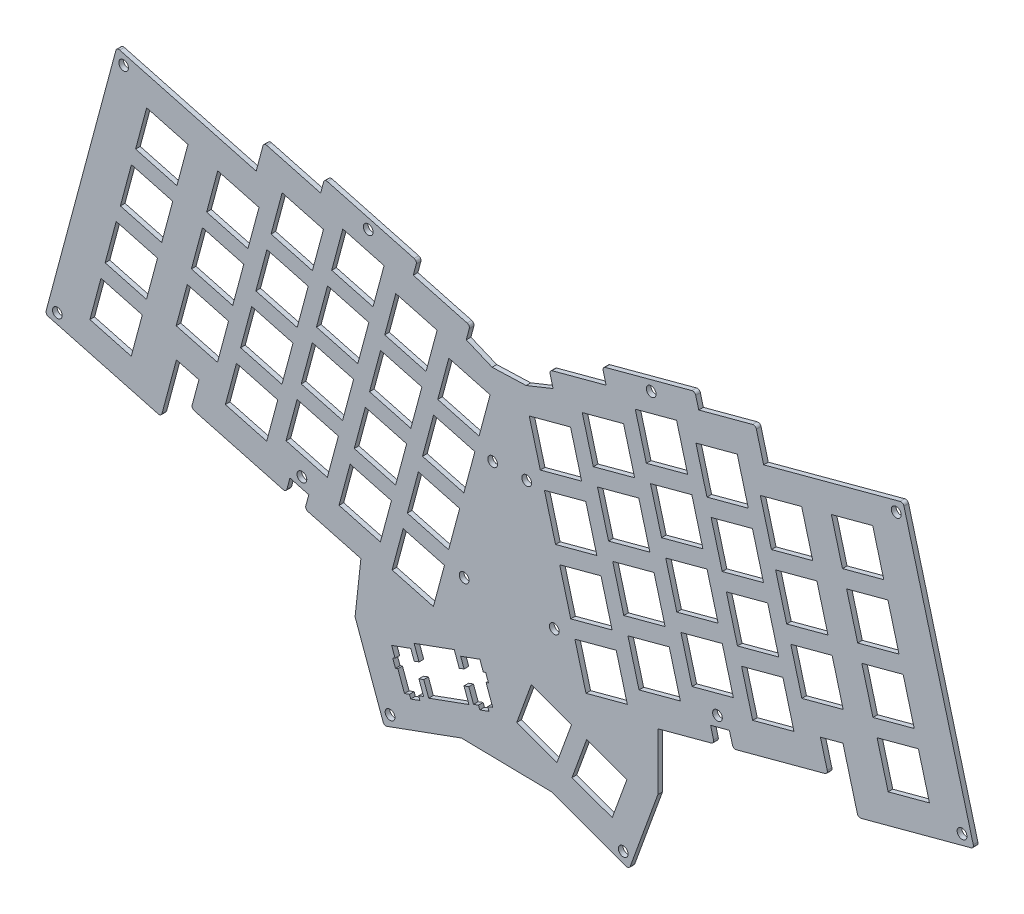
SolidWorks part; units mm, degrees
ref_plane "Front Plane" through (0, 0, 0) normal (0, 0, 1) x (1, 0, 0)
ref_plane "Top Plane" through (0, 0, 0) normal (0, 1, 0) x (1, 0, 0)
ref_plane "Right Plane" through (0, 0, 0) normal (1, 0, 0) x (0, 0, -1)
sketch "Model" plane through (0, 0, 0) normal (0, 0, 1) x (1, 0, 0)
  line L0 (282.165, 226.202) -> (288.4436, 227.8841) construction
  line L1 (267.373, 281.405) -> (273.6516, 283.0871) construction
  line L2 (195.392, 284.0785) -> (194.5766, 287.1211) construction
  line L3 (100.681, 283.685) -> (101.4961, 286.7277) construction
  line L4 (168.22, 168.742) -> (181.234, 164.006)
  line L5 (181.234, 164.006) -> (185.972, 177.021)
  line L6 (185.972, 177.021) -> (172.956, 181.758)
  line L7 (172.956, 181.758) -> (168.22, 168.742)
  line L8 (132.176, 184.752) -> (133.281, 181.717)
  line L9 (133.281, 181.717) -> (131.706, 181.144)
  line L10 (131.706, 181.144) -> (130.099, 185.56)
  line L11 (130.099, 185.56) -> (117.085, 180.823)
  line L12 (117.085, 180.823) -> (118.692, 176.407)
  line L13 (118.692, 176.407) -> (117.118, 175.834)
  line L14 (117.118, 175.834) -> (116.013, 178.869)
  line L15 (116.013, 178.869) -> (109.812, 176.612)
  line L16 (109.812, 176.612) -> (110.917, 173.576)
  line L17 (110.917, 173.576) -> (110.141, 173.294)
  line L18 (110.141, 173.294) -> (111.048, 170.804)
  line L19 (111.048, 170.804) -> (111.822, 171.086)
  line L20 (111.822, 171.086) -> (113.968, 165.194)
  line L21 (113.968, 165.194) -> (115.588, 165.784)
  line L22 (115.588, 165.784) -> (115.999, 164.656)
  line L23 (115.999, 164.656) -> (118.959, 165.734)
  line L24 (118.959, 165.734) -> (118.549, 166.861)
  line L25 (118.549, 166.861) -> (120.169, 167.452)
  line L26 (120.169, 167.452) -> (118.641, 171.651)
  line L27 (118.641, 171.651) -> (120.215, 172.224)
  line L28 (120.215, 172.224) -> (121.821, 167.809)
  line L29 (121.821, 167.809) -> (134.837, 172.545)
  line L30 (134.837, 172.545) -> (133.23, 176.962)
  line L31 (133.23, 176.962) -> (134.804, 177.535)
  line L32 (134.804, 177.535) -> (136.332, 173.335)
  line L33 (136.332, 173.335) -> (137.953, 173.925)
  line L34 (137.953, 173.925) -> (138.363, 172.796)
  line L35 (138.363, 172.796) -> (141.323, 173.874)
  line L36 (141.323, 173.874) -> (140.913, 175.001)
  line L37 (140.913, 175.001) -> (142.533, 175.592)
  line L38 (142.533, 175.592) -> (140.389, 181.483)
  line L39 (140.389, 181.483) -> (141.165, 181.766)
  line L40 (141.165, 181.766) -> (140.258, 184.256)
  line L41 (140.258, 184.256) -> (139.484, 183.974)
  line L42 (139.484, 183.974) -> (138.378, 187.009)
  line L43 (138.378, 187.009) -> (132.176, 184.752)
  line L44 (150.319, 175.258) -> (163.333, 170.521)
  line L45 (163.333, 170.521) -> (168.071, 183.535)
  line L46 (168.071, 183.535) -> (155.055, 188.273)
  line L47 (155.055, 188.273) -> (150.319, 175.258)
  line L48 (109.952, 197.835) -> (123.33, 194.251)
  line L49 (123.33, 194.251) -> (126.916, 207.629)
  line L50 (126.916, 207.629) -> (113.537, 211.213)
  line L51 (113.537, 211.213) -> (109.952, 197.835)
  line L52 (169.157, 208.022) -> (172.741, 194.644)
  line L53 (172.741, 194.644) -> (186.119, 198.228)
  line L54 (186.119, 198.228) -> (182.535, 211.607)
  line L55 (182.535, 211.607) -> (169.157, 208.022)
  line L56 (92.7848, 207.366) -> (106.163, 203.781)
  line L57 (106.163, 203.781) -> (109.747, 217.159)
  line L58 (109.747, 217.159) -> (96.369, 220.744)
  line L59 (96.369, 220.744) -> (92.7848, 207.366)
  line L60 (186.326, 217.552) -> (189.91, 204.174)
  line L61 (189.91, 204.174) -> (203.288, 207.759)
  line L62 (203.288, 207.759) -> (199.704, 221.137)
  line L63 (199.704, 221.137) -> (186.326, 217.552)
  line L64 (114.883, 216.236) -> (128.261, 212.652)
  line L65 (128.261, 212.652) -> (131.845, 226.03)
  line L66 (131.845, 226.03) -> (118.467, 229.614)
  line L67 (118.467, 229.614) -> (114.883, 216.236)
  line L68 (164.226, 226.423) -> (167.812, 213.045)
  line L69 (167.812, 213.045) -> (181.19, 216.629)
  line L70 (181.19, 216.629) -> (177.604, 230.007)
  line L71 (177.604, 230.007) -> (164.226, 226.423)
  line L72 (75.6158, 216.896) -> (88.9938, 213.312)
  line L73 (88.9938, 213.312) -> (92.5781, 226.69)
  line L74 (92.5781, 226.69) -> (79.2, 230.274)
  line L75 (79.2, 230.274) -> (75.6158, 216.896)
  line L76 (55.9827, 217.227) -> (69.3607, 213.643)
  line L77 (69.3607, 213.643) -> (72.9449, 227.021)
  line L78 (72.9449, 227.021) -> (59.5672, 230.605)
  line L79 (59.5672, 230.605) -> (55.9827, 217.227)
  line L80 (203.494, 227.083) -> (207.078, 213.705)
  line L81 (207.078, 213.705) -> (220.457, 217.29)
  line L82 (220.457, 217.29) -> (216.872, 230.668)
  line L83 (216.872, 230.668) -> (203.494, 227.083)
  line L84 (223.128, 227.414) -> (226.712, 214.036)
  line L85 (226.712, 214.036) -> (240.09, 217.62)
  line L86 (240.09, 217.62) -> (236.506, 230.998)
  line L87 (236.506, 230.998) -> (223.128, 227.414)
  line L88 (12.1157, 219.121) -> (25.4937, 215.536)
  line L89 (25.4937, 215.536) -> (29.078, 228.914)
  line L90 (29.078, 228.914) -> (15.7, 232.499)
  line L91 (15.7, 232.499) -> (12.1157, 219.121)
  line L92 (266.995, 229.307) -> (270.579, 215.929)
  line L93 (270.579, 215.929) -> (283.957, 219.513)
  line L94 (283.957, 219.513) -> (280.373, 232.891)
  line L95 (280.373, 232.891) -> (266.995, 229.307)
  line L96 (97.7138, 225.767) -> (111.092, 222.183)
  line L97 (111.092, 222.183) -> (114.677, 235.56)
  line L98 (114.677, 235.56) -> (101.299, 239.145)
  line L99 (101.299, 239.145) -> (97.7138, 225.767)
  line L100 (181.394, 235.953) -> (184.98, 222.575)
  line L101 (184.98, 222.575) -> (198.357, 226.159)
  line L102 (198.357, 226.159) -> (194.773, 239.538)
  line L103 (194.773, 239.538) -> (181.394, 235.953)
  line L104 (40.0473, 231.357) -> (53.425, 227.773)
  line L105 (53.425, 227.773) -> (57.0096, 241.151)
  line L106 (57.0096, 241.151) -> (43.6316, 244.735)
  line L107 (43.6316, 244.735) -> (40.0473, 231.357)
  line L108 (239.062, 241.545) -> (242.648, 228.166)
  line L109 (242.648, 228.166) -> (256.024, 231.75)
  line L110 (256.024, 231.75) -> (252.44, 245.128)
  line L111 (252.44, 245.128) -> (239.062, 241.545)
  line L112 (119.814, 234.637) -> (133.192, 231.053)
  line L113 (133.192, 231.053) -> (136.776, 244.431)
  line L114 (136.776, 244.431) -> (123.396, 248.015)
  line L115 (123.396, 248.015) -> (119.814, 234.637)
  line L116 (159.297, 244.824) -> (162.88, 231.445)
  line L117 (162.88, 231.445) -> (176.258, 235.03)
  line L118 (176.258, 235.03) -> (172.675, 248.408)
  line L119 (172.675, 248.408) -> (159.297, 244.824)
  line L120 (80.5462, 235.297) -> (93.9243, 231.713)
  line L121 (93.9243, 231.713) -> (97.5099, 245.091)
  line L122 (97.5099, 245.091) -> (84.1304, 248.675)
  line L123 (84.1304, 248.675) -> (80.5462, 235.297)
  line L124 (60.912, 235.628) -> (74.2901, 232.044)
  line L125 (74.2901, 232.044) -> (77.8757, 245.422)
  line L126 (77.8757, 245.422) -> (64.4977, 249.006)
  line L127 (64.4977, 249.006) -> (60.912, 235.628)
  line L128 (198.563, 245.484) -> (202.147, 232.106)
  line L129 (202.147, 232.106) -> (215.525, 235.692)
  line L130 (215.525, 235.692) -> (211.941, 249.069)
  line L131 (211.941, 249.069) -> (198.563, 245.484)
  line L132 (218.196, 245.814) -> (221.782, 232.436)
  line L133 (221.782, 232.436) -> (235.16, 236.021)
  line L134 (235.16, 236.021) -> (231.574, 249.399)
  line L135 (231.574, 249.399) -> (218.196, 245.814)
  line L136 (17.045, 237.521) -> (30.423, 233.937)
  line L137 (30.423, 233.937) -> (34.0086, 247.315)
  line L138 (34.0086, 247.315) -> (20.6306, 250.899)
  line L139 (20.6306, 250.899) -> (17.045, 237.521)
  line L140 (262.063, 247.708) -> (265.649, 234.33)
  line L141 (265.649, 234.33) -> (279.026, 237.914)
  line L142 (279.026, 237.914) -> (275.442, 251.292)
  line L143 (275.442, 251.292) -> (262.063, 247.708)
  line L144 (102.646, 244.168) -> (116.024, 240.584)
  line L145 (116.024, 240.584) -> (119.607, 253.962)
  line L146 (119.607, 253.962) -> (106.229, 257.546)
  line L147 (106.229, 257.546) -> (102.646, 244.168)
  line L148 (176.465, 254.354) -> (180.049, 240.976)
  line L149 (180.049, 240.976) -> (193.427, 244.56)
  line L150 (193.427, 244.56) -> (189.843, 257.938)
  line L151 (189.843, 257.938) -> (176.465, 254.354)
  line L152 (44.9778, 249.759) -> (58.3558, 246.174)
  line L153 (58.3558, 246.174) -> (61.94, 259.553)
  line L154 (61.94, 259.553) -> (48.562, 263.136)
  line L155 (48.562, 263.136) -> (44.9778, 249.759)
  line L156 (234.133, 259.945) -> (237.717, 246.567)
  line L157 (237.717, 246.567) -> (251.095, 250.151)
  line L158 (251.095, 250.151) -> (247.511, 263.529)
  line L159 (247.511, 263.529) -> (234.133, 259.945)
  line L160 (124.743, 253.038) -> (138.122, 249.454)
  line L161 (138.122, 249.454) -> (141.707, 262.832)
  line L162 (141.707, 262.832) -> (128.329, 266.416)
  line L163 (128.329, 266.416) -> (124.743, 253.038)
  line L164 (154.365, 263.224) -> (157.951, 249.845)
  line L165 (157.951, 249.845) -> (171.329, 253.432)
  line L166 (171.329, 253.432) -> (167.743, 266.809)
  line L167 (167.743, 266.809) -> (154.365, 263.224)
  line L168 (85.477, 253.699) -> (98.855, 250.114)
  line L169 (98.855, 250.114) -> (102.439, 263.492)
  line L170 (102.439, 263.492) -> (89.0612, 267.076)
  line L171 (89.0612, 267.076) -> (85.477, 253.699)
  line L172 (65.8442, 254.03) -> (79.2219, 250.443)
  line L173 (79.2219, 250.443) -> (82.8065, 263.823)
  line L174 (82.8065, 263.823) -> (69.427, 267.407)
  line L175 (69.427, 267.407) -> (65.8442, 254.03)
  line L176 (193.632, 263.885) -> (197.218, 250.507)
  line L177 (197.218, 250.507) -> (210.596, 254.092)
  line L178 (210.596, 254.092) -> (207.01, 267.47)
  line L179 (207.01, 267.47) -> (193.632, 263.885)
  line L180 (213.267, 264.215) -> (216.851, 250.837)
  line L181 (216.851, 250.837) -> (230.229, 254.422)
  line L182 (230.229, 254.422) -> (226.645, 267.8)
  line L183 (226.645, 267.8) -> (213.267, 264.215)
  line L184 (21.977, 255.922) -> (35.355, 252.338)
  line L185 (35.355, 252.338) -> (38.9378, 265.716)
  line L186 (38.9378, 265.716) -> (25.5598, 269.3)
  line L187 (25.5598, 269.3) -> (21.977, 255.922)
  line L188 (257.132, 266.109) -> (260.718, 252.729)
  line L189 (260.718, 252.729) -> (274.096, 256.315)
  line L190 (274.096, 256.315) -> (270.512, 269.693)
  line L191 (270.512, 269.693) -> (257.132, 266.109)
  line L192 (107.575, 262.569) -> (120.953, 258.984)
  line L193 (120.953, 258.984) -> (124.539, 272.362)
  line L194 (124.539, 272.362) -> (111.161, 275.947)
  line L195 (111.161, 275.947) -> (107.575, 262.569)
  line L196 (171.534, 272.755) -> (175.118, 259.377)
  line L197 (175.118, 259.377) -> (188.496, 262.961)
  line L198 (188.496, 262.961) -> (184.912, 276.339)
  line L199 (184.912, 276.339) -> (171.534, 272.755)
  line L200 (49.9071, 268.159) -> (63.2852, 264.575)
  line L201 (63.2852, 264.575) -> (66.8708, 277.953)
  line L202 (66.8708, 277.953) -> (53.4928, 281.537)
  line L203 (53.4928, 281.537) -> (49.9071, 268.159)
  line L204 (229.201, 278.346) -> (232.786, 264.968)
  line L205 (232.786, 264.968) -> (246.164, 268.554)
  line L206 (246.164, 268.554) -> (242.579, 281.932)
  line L207 (242.579, 281.932) -> (229.201, 278.346)
  line L208 (90.4074, 272.099) -> (103.785, 268.515)
  line L209 (103.785, 268.515) -> (107.37, 281.893)
  line L210 (107.37, 281.893) -> (93.992, 285.477)
  line L211 (93.992, 285.477) -> (90.4074, 272.099)
  line L212 (70.7732, 272.43) -> (84.1513, 268.844)
  line L213 (84.1513, 268.844) -> (87.7369, 282.222)
  line L214 (87.7369, 282.222) -> (74.3589, 285.808)
  line L215 (74.3589, 285.808) -> (70.7732, 272.43)
  line L216 (188.703, 282.286) -> (192.286, 268.908)
  line L217 (192.286, 268.908) -> (205.664, 272.493)
  line L218 (205.664, 272.493) -> (202.081, 285.871)
  line L219 (202.081, 285.871) -> (188.703, 282.286)
  line L220 (208.336, 282.616) -> (211.92, 269.238)
  line L221 (211.92, 269.238) -> (225.298, 272.822)
  line L222 (225.298, 272.822) -> (221.714, 286.2)
  line L223 (221.714, 286.2) -> (208.336, 282.616)
  line L224 (26.9062, 274.323) -> (40.284, 270.739)
  line L225 (40.284, 270.739) -> (43.8697, 284.117)
  line L226 (43.8697, 284.117) -> (30.4919, 287.701)
  line L227 (30.4919, 287.701) -> (26.9062, 274.323)
  line L228 (252.203, 284.508) -> (255.786, 271.131)
  line L229 (255.786, 271.131) -> (269.165, 274.716)
  line L230 (269.165, 274.716) -> (265.581, 288.094)
  line L231 (265.581, 288.094) -> (252.203, 284.508)
  line L232 (37.1808, 285.909) -> (37.996, 288.9517) construction
  line L233 (28.6991, 281.012) -> (22.4207, 282.6948) construction
  line L234 (18.8047, 217.3285) -> (17.9893, 214.2859) construction
  line L235 (13.9078, 225.81) -> (7.6293, 227.4922) construction
  line L236 (277.268, 217.721) -> (278.0831, 214.6783) construction
  line L237 (271.2033, 292.224) -> (291.0512, 218.1525) construction
  line L238 (241.3027, 224.5444) -> (243.7675, 215.3441) construction
  line L239 (81.0479, 284.015) -> (81.8635, 287.0576) construction
  line L240 (181.234, 164.006) -> (184.194, 162.9285) construction
  line L241 (91.0631, 284.5916) -> (72.6639, 289.5236) construction
  line L242 (117.85, 274.1545) -> (118.6654, 277.1971) construction
  line L243 (135.018, 264.624) -> (135.8331, 267.6667) construction
  line L244 (161.054, 265.0165) -> (160.2386, 268.0591) construction
  line L245 (178.223, 274.547) -> (177.4079, 277.5897) construction
  line L246 (215.025, 284.408) -> (214.2099, 287.4507) construction
  line L247 (258.892, 286.301) -> (258.2357, 288.7493) construction
  line L248 (196.599, 205.9665) -> (197.4144, 202.9239) construction
  line L249 (92.2965, 289.1937) -> (110.6958, 284.2617) construction
  line L250 (213.7675, 215.4975) -> (214.5828, 212.4548) construction
  line L251 (233.401, 215.828) -> (234.2161, 212.7853) construction
  line L252 (62.6717, 215.435) -> (61.8566, 212.3923) construction
  line L253 (82.3048, 215.104) -> (81.4897, 212.0613) construction
  line L254 (99.4739, 205.5735) -> (98.6586, 202.5309) construction
  line L255 (35.8867, 229.2106) -> (54.7701, 224.1516) construction
  line L256 (60.1818, 279.745) -> (60.9969, 282.7877) construction
  line L257 (72.6639, 289.5236) -> (70.1982, 280.3232) construction
  line L258 (105.8147, 195.273) -> (104.0964, 179.4507) construction
  line L259 (52.3052, 214.9511) -> (54.7701, 224.1516) construction
  line L260 (260.1862, 229.6041) -> (265.1156, 211.2042) construction
  line L261 (203.777, 289.5866) -> (185.3762, 284.6556) construction
  line L262 (30.9571, 210.8115) -> (35.8867, 229.2106) construction
  line L263 (141.707, 262.832) -> (142.5224, 265.8746) construction
  line L264 (154.365, 263.224) -> (153.5495, 266.2666) construction
  line L265 (181.234, 164.006) -> (180.1565, 161.046) construction
  line L266 (92.2965, 289.1937) -> (91.0631, 284.5916) construction
  line L267 (169.4396, 270.5248) -> (150.6904, 265.5004) construction
  line L268 (110.6958, 284.2617) -> (109.4634, 279.6637) construction
  line L269 (127.8626, 274.7318) -> (126.6303, 270.1341) construction
  line L270 (127.8626, 274.7318) -> (109.4634, 279.6637) construction
  line L271 (260.1862, 229.6041) -> (241.3027, 224.5444) construction
  line L272 (126.6303, 270.1341) -> (145.3813, 265.1084) construction
  line L273 (185.3762, 284.6556) -> (186.6084, 280.0546) construction
  line L274 (142.3447, 270.8715) -> (153.3719, 271.2634)
  line L275 (203.777, 289.5866) -> (205.0099, 284.986) construction
  line L276 (168.2073, 275.1248) -> (169.4396, 270.5248) construction
  line L277 (205.0099, 284.986) -> (223.4098, 289.9154) construction
  line L278 (223.4098, 289.9154) -> (226.0339, 280.1206) construction
  line L279 (186.6084, 280.0546) -> (168.2073, 275.1248) construction
  line L280 (104.0964, 179.4507) -> (110.9864, 160.5147) construction
  line L281 (152.687, 181.7655) -> (183.603, 170.5135) construction
  line L282 (110.5015, 171.0598) -> (141.4185, 182.3092) construction
  line L283 (27.2858, 222.225) -> (33.5644, 220.5428) construction
  line L284 (90.3394, 209.6904) -> (72.6399, 214.4322) construction
  line L285 (71.4079, 209.8335) -> (72.6399, 214.4322) construction
  line L286 (89.1069, 205.0898) -> (90.3394, 209.6904) construction
  line L287 (89.1069, 205.0898) -> (107.1497, 200.256) construction
  line L288 (107.1497, 200.256) -> (105.8147, 195.273) construction
  line L289 (110.9864, 160.5147) -> (131.4289, 167.9529) construction
  line L290 (71.4079, 209.8335) -> (52.3052, 214.9511) construction
  line L291 (5.0216, 217.7602) -> (25.0282, 292.4264) construction
  line L292 (130.099, 185.56) -> (121.821, 167.809) construction
  line L293 (190.0384, 195.7708) -> (190.0096, 178.9037) construction
  line L294 (235.89, 280.139) -> (235.2337, 282.5873) construction
  line L295 (162.6744, 167.408) -> (183.1165, 159.9688) construction
  line L296 (131.4289, 167.9529) -> (162.6744, 167.408) construction
  line L297 (5.0216, 217.7602) -> (30.9571, 210.8115) construction
  line L298 (46.7361, 229.565) -> (45.921, 226.5223) construction
  line L299 (265.1156, 211.2042) -> (291.0512, 218.1525) construction
  line L300 (25.0282, 292.4264) -> (70.1982, 280.3232) construction
  line L301 (226.0339, 280.1206) -> (258.2357, 288.7493) construction
  line L302 (258.2357, 288.7493) -> (271.2033, 292.224) construction
  line L303 (128.329, 170.177) -> (129.4061, 167.2169) construction
  line L304 (249.336, 229.958) -> (250.1513, 226.9153) construction
  line L305 (268.787, 222.618) -> (262.5084, 220.9359) construction
  line L306 (109.952, 197.835) -> (106.7322, 198.6976) construction
  line L307 (-2.3268, 213.5174) -> (20.7855, 299.7748)
  line L308 (186.119, 198.228) -> (189.1617, 199.0431) construction
  line L309 (206.9661, 205.4835) -> (188.7445, 200.6005) construction
  line L310 (188.7445, 200.6005) -> (190.0384, 195.7708) construction
  line L311 (20.7855, 299.7748) -> (65.9558, 287.6716)
  line L312 (68.4216, 296.8725) -> (65.9558, 287.6716)
  line L313 (86.821, 291.9405) -> (68.4216, 296.8725)
  line L314 (88.0544, 296.5426) -> (86.821, 291.9405)
  line L315 (88.0544, 296.5426) -> (118.0445, 288.5037)
  line L316 (118.0445, 288.5037) -> (116.8121, 283.9057)
  line L317 (135.2113, 278.9738) -> (116.8121, 283.9057)
  line L318 (135.2113, 278.9738) -> (133.9791, 274.3762)
  line L319 (133.9791, 274.3762) -> (142.3447, 270.8715)
  line L320 (153.3719, 271.2634) -> (162.0915, 274.7674)
  line L321 (20.7855, 299.7748) -> (25.0282, 292.4264) construction
  line L322 (160.859, 279.3678) -> (162.0915, 274.7674)
  line L323 (179.2607, 284.2977) -> (160.859, 279.3678)
  line L324 (178.0286, 288.8984) -> (179.2607, 284.2977)
  line L325 (208.0195, 296.9352) -> (178.0286, 288.8984)
  line L326 (208.0195, 296.9352) -> (209.2525, 292.3342)
  line L327 (209.2525, 292.3342) -> (227.6528, 297.2637)
  line L328 (227.6528, 297.2637) -> (230.2767, 287.4692)
  line L329 (230.2767, 287.4692) -> (275.4459, 299.5725)
  line L330 (298.3998, 213.9096) -> (294.5027, 216.1597) construction
  line L331 (275.4459, 299.5725) -> (298.3998, 213.9096)
  line L332 (260.8726, 203.856) -> (298.3998, 213.9096)
  line L333 (255.9433, 222.2556) -> (260.8726, 203.856)
  line L334 (255.9433, 222.2556) -> (248.6509, 220.3017)
  line L335 (183.1165, 159.9688) -> (190.0096, 178.9037) construction
  line L336 (248.6509, 220.3017) -> (251.1158, 211.1012)
  line L337 (220.4222, 202.8783) -> (251.1158, 211.1012)
  line L338 (219.1898, 207.4775) -> (220.4222, 202.8783)
  line L339 (213.082, 205.8412) -> (219.1898, 207.4775)
  line L340 (206.9661, 205.4835) -> (205.7333, 210.084) construction
  line L341 (223.4323, 214.8256) -> (224.6648, 210.2265) construction
  line L342 (205.7333, 210.084) -> (223.4323, 214.8256) construction
  line L343 (214.3147, 201.2411) -> (213.082, 205.8412)
  line L344 (214.3147, 201.2411) -> (196.0393, 196.3437)
  line L345 (224.6648, 210.2265) -> (243.7675, 215.3441) construction
  line L346 (196.0393, 196.3437) -> (196.0078, 177.8406)
  line L347 (150.6904, 265.5004) -> (170.7656, 190.6076) construction
  line L348 (186.7023, 152.2789) -> (196.0078, 177.8406)
  line L349 (161.566, 161.4264) -> (186.7023, 152.2789)
  line L350 (132.4358, 161.9344) -> (161.566, 161.4264)
  line L351 (107.3996, 152.8248) -> (132.4358, 161.9344)
  line L352 (97.9807, 178.7109) -> (107.3996, 152.8248)
  line L353 (99.8582, 195.9979) -> (97.9807, 178.7109)
  line L354 (141.707, 262.832) -> (154.365, 263.224) construction
  line L355 (81.7586, 200.8468) -> (99.8582, 195.9979)
  line L356 (81.7586, 200.8468) -> (82.9911, 205.4475)
  line L357 (82.9911, 205.4475) -> (76.8829, 207.0839)
  line L358 (75.6509, 202.4852) -> (76.8829, 207.0839)
  line L359 (75.6509, 202.4852) -> (44.9569, 210.7082)
  line L360 (44.9569, 210.7082) -> (47.4218, 219.9086)
  line L361 (40.1295, 221.8623) -> (47.4218, 219.9086)
  line L362 (35.1999, 203.4631) -> (40.1295, 221.8623)
  line L363 (-2.3268, 213.5174) -> (35.1999, 203.4631)
  line L364 (20.7855, 299.7748) -> (23.0356, 295.8777) construction
  line L365 (142.5224, 265.8746) -> (153.5495, 266.2666) construction
  line L366 (275.4459, 299.5725) -> (271.2033, 292.224) construction
  line L367 (291.0512, 218.1525) -> (298.3998, 213.9096) construction
  line L368 (-2.3268, 213.5174) -> (5.0216, 217.7602) construction
  line L369 (107.3996, 152.8248) -> (110.9864, 160.5147) construction
  line L370 (183.1165, 159.9688) -> (186.7023, 152.2789) construction
  line L371 (107.3996, 152.8248) -> (109.3018, 156.903) construction
  line L372 (184.8006, 156.3573) -> (186.7023, 152.2789) construction
  line L373 (106.163, 203.781) -> (189.91, 204.174) construction
  line L374 (101.4961, 286.7277) -> (103.0495, 292.5232) construction
  line L375 (194.5766, 287.1211) -> (193.0241, 292.9168) construction
  line L376 (23.0356, 295.8777) -> (23.8591, 298.9513) construction
  line L377 (193.0241, 292.9168) -> (193.8474, 289.8432) construction
  line L378 (214.5828, 212.4548) -> (216.1359, 206.6593) construction
  line L379 (103.0495, 292.5232) -> (102.2257, 289.4497) construction
  line L380 (275.4459, 299.5725) -> (273.1959, 295.6754) construction
  line L381 (-2.3268, 213.5174) -> (1.5702, 215.7675) construction
  line L382 (81.4897, 212.0613) -> (79.937, 206.2657) construction
  line L383 (81.4897, 212.0613) -> (79.937, 206.2657) construction
  line L384 (214.5828, 212.4548) -> (216.1359, 206.6593) construction
  line L385 (145.3813, 265.1084) -> (125.265, 190.0622) construction
  line L386 (190.0384, 195.7708) -> (170.7656, 190.6076) construction
  line L387 (148.0359, 266.0706) -> (148.0365, 203.9775) construction
  line L388 (105.8147, 195.273) -> (125.265, 190.0622) construction
  line L389 (104.0964, 179.4507) -> (140.9309, 192.8582) construction
  line L390 (190.0096, 178.9037) -> (153.1726, 192.3111) construction
  line L391 (152.687, 181.7655) -> (149.727, 182.8428) construction
  line L392 (162.6744, 167.408) -> (146.281, 173.3738) construction
  line L393 (153.1726, 192.3111) -> (146.281, 173.3738) construction
  line L394 (131.4289, 167.9529) -> (147.823, 173.9234) construction
  line L395 (141.4185, 182.3092) -> (144.3786, 183.3863) construction
  line L396 (140.9309, 192.8582) -> (147.823, 173.9234) construction
  line L397 (110.5015, 171.0598) -> (107.5414, 169.9827) construction
  line L398 (123.592, 183.1915) -> (122.5136, 186.1545) construction
  line L399 (105.8147, 195.273) -> (183.187, 229.264) construction
  line L400 (171.073, 185.7954) -> (164.1828, 166.8591) construction
  line L401 (112.8845, 228.8715) -> (190.0384, 195.7708) construction
  line L402 (105.8147, 195.273) -> (133.2811, 207.3395) construction
  line L403 (162.4685, 207.5989) -> (190.0384, 195.7708) construction
  line L404 (136.776, 244.431) -> (159.297, 244.824) construction
  line L405 (136.776, 244.431) -> (142.5224, 244.5313) construction
  line L406 (159.297, 244.824) -> (153.5495, 244.7237) construction
  line L407 (79.937, 206.2657) -> (80.7604, 209.3393) construction
  line L408 (216.1359, 206.6593) -> (215.3122, 209.7329) construction
  line L425 (164.1828, 166.8591) -> (183.1165, 159.9688) construction
  line L426 (190.0096, 178.9037) -> (171.073, 185.7954) construction
  line L427 (99.8582, 195.9979) -> (99.8582, 195.9979) construction
  line L428 (99.8582, 195.9979) -> (97.9807, 178.7109) construction
  line L429 (150.6904, 265.5004) -> (145.3813, 265.1084) construction
  line L430 (149.6841, 271.4425) -> (145.9529, 271.1669) construction
  line L431 (133.9791, 274.3762) -> (145.9529, 271.1669) construction
  line L432 (162.0915, 274.7674) -> (149.6841, 271.4425) construction
  line L433 (256.6828, 294.5448) -> (275.4459, 299.5725) construction
  line L434 (230.2767, 287.4692) -> (256.6828, 294.5448) construction
  line L435 (196.0393, 196.3437) -> (196.0393, 196.3437) construction
  line L436 (196.0393, 196.3437) -> (196.0078, 177.8406) construction
  circle A0 centre (23.0356, 295.8777) radius 1.575
  circle A1 centre (109.3018, 156.903) radius 1.575
  circle A2 centre (184.8006, 156.3573) radius 1.575
  circle A3 centre (193.8474, 289.8432) radius 1.575
  circle A4 centre (102.2257, 289.4497) radius 1.575
  circle A5 centre (273.1959, 295.6754) radius 1.5916
  circle A6 centre (1.5702, 215.7675) radius 1.575
  circle A7 centre (294.5027, 216.1597) radius 1.5916
  circle A8 centre (80.7604, 209.3393) radius 1.575
  circle A9 centre (215.3122, 209.7329) radius 1.575
  circle A10 centre (133.2811, 207.3395) radius 1.575
  circle A11 centre (162.4685, 207.5989) radius 1.575
  circle A12 centre (142.5224, 244.5313) radius 1.575
  circle A13 centre (153.5495, 244.7237) radius 1.575
  point P253 (61.8566, 212.3923)
  point P289 (81.8635, 287.0576)
  point P293 (194.5766, 287.1211)
  point P295 (101.4961, 286.7277)
  point P361 (125.96, 176.6845)
  point P362 (125.96, 176.6845)
  point P374 (214.5828, 212.4548)
  point P377 (234.2161, 212.7853)
  point P378 (177.4079, 277.5897)
  point P386 (214.2099, 287.4507)
  dimension "D5" = 6
  dimension "D4" = 3.15
  dimension "D7" = 30.011
  dimension "D8" = 30
  dimension "D1" = 9.5249
  dimension "D2" = 6.5
  dimension "D3" = 5
  dimension "D6" = 4.5
extrude "Boss-Extrude1" add sketch "Model" against normal blind 1.5
fillet "Fillet2" radius 1 22 edges at (-2.3268, 213.5174, -0.75) (44.9569, 210.7082, -0.75) (35.1999, 203.4631, -0.75) (75.6509, 202.4852, -0.75) (81.7586, 200.8468, -0.75) (107.3996, 152.8248, -0.75) (220.4222, 202.8783, -0.75) (214.3147, 201.2411, -0.75) (186.7023, 152.2789, -0.75) (260.8726, 203.856, -0.75) (251.1158, 211.1012, -0.75) (298.3998, 213.9096, -0.75) (275.4459, 299.5725, -0.75) (227.6528, 297.2637, -0.75) (208.0195, 296.9352, -0.75) (178.0286, 288.8984, -0.75) (160.859, 279.3678, -0.75) (135.2113, 278.9738, -0.75) (118.0445, 288.5037, -0.75) (88.0544, 296.5426, -0.75) (68.4216, 296.8725, -0.75) (20.7855, 299.7748, -0.75)
